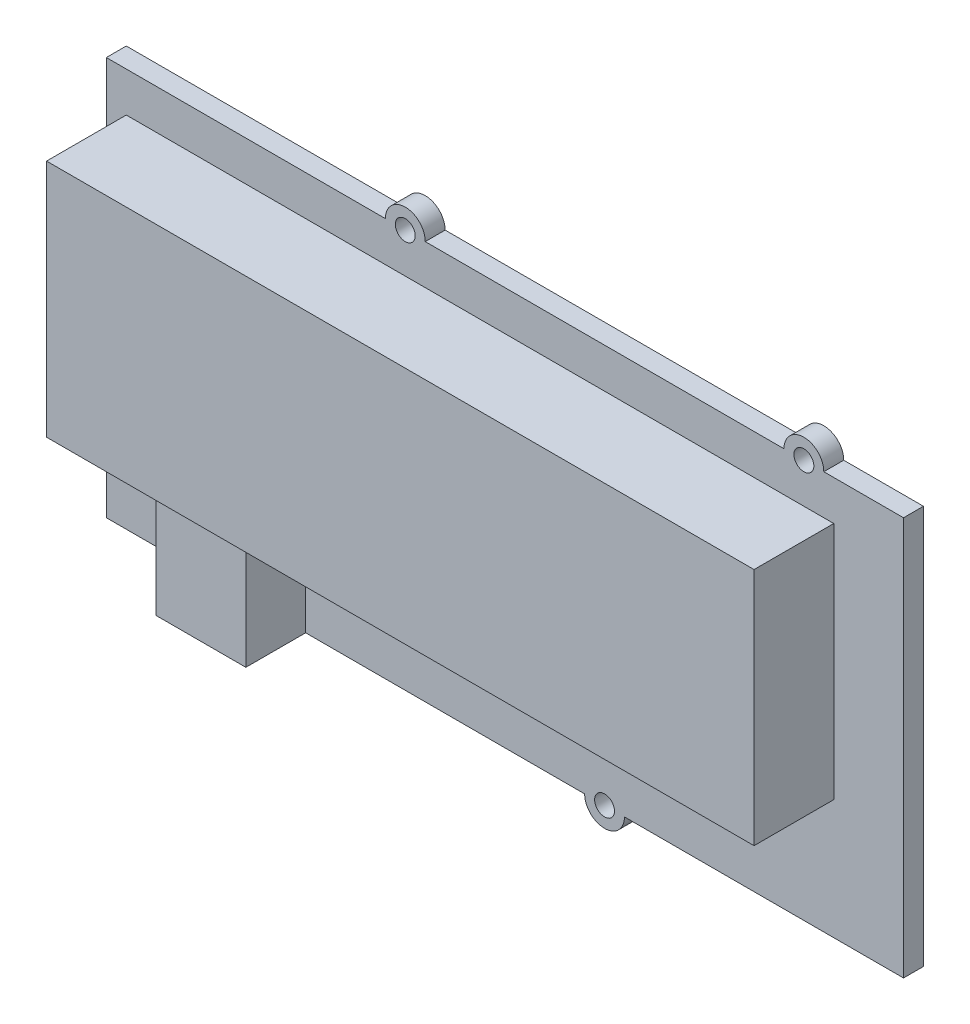
SolidWorks part; units mm, degrees
ref_plane "Plan de face" through (0, 0, 0) normal (0, 0, 1) x (1, 0, 0)
ref_plane "Plan de dessus" through (0, 0, 0) normal (0, 1, 0) x (1, 0, 0)
ref_plane "Plan de droite" through (0, 0, 0) normal (1, 0, 0) x (0, 0, -1)
sketch "Esquisse1" plane through (0, 0, 0) normal (0, 0, 1) x (1, 0, 0)
  line L0 (-47.6002, 9.7568) -> (-19.6002, 9.7568)
  line L2 (-47.6002, 9.7568) -> (-47.6002, -30.2432)
  line L4 (32.3998, 9.7568) -> (32.3998, -30.2432)
  line L5 (-15.6002, 9.7568) -> (20.3998, 9.7568)
  line L6 (24.3998, 9.7568) -> (32.3998, 9.7568)
  line L7 (32.3998, -30.2432) -> (4.3998, -30.2432)
  line L8 (-47.6002, -30.2432) -> (0.3998, -30.2432)
  circle A0 centre (22.3998, 9.7568) radius 1
  circle A1 centre (-17.6002, 9.7568) radius 1
  circle A2 centre (2.3998, -30.2432) radius 1
  arc A5 (-19.6002, 9.7568) -> (-15.6002, 9.7568) centre (-17.6002, 9.7568) cw
  arc A6 (20.3998, 9.7568) -> (24.3998, 9.7568) centre (22.3998, 9.7568) cw
  arc A8 (0.3998, -30.2432) -> (4.3998, -30.2432) centre (2.3998, -30.2432) ccw
  dimension "D3" = 2
  dimension "D5" = 2
  dimension "D7" = 2
  dimension "D8" = 30
  dimension "D1" = 80
  dimension "D2" = 40
  dimension "D4" = 10
  dimension "D6" = 40
extrude "Boss.-Extru.1" add sketch "Esquisse1" along normal blind 2 contours L8 A8 L7 L4 L6 A6 L5 A5 L0 L2 A0 A1 A2
sketch "Esquisse2" plane through (0, 0, 2) normal (0, 0, 1) x (1, 0, 0)
  line L0 (-47.6002, 9.7568) -> (-47.6002, -30.2432) construction
  line L1 (-45.6002, 5.7568) -> (25.3998, 5.7568)
  line L2 (-45.6002, 5.7568) -> (-45.6002, -18.2432)
  line L3 (-45.6002, -18.2432) -> (25.3998, -18.2432)
  line L4 (25.3998, 5.7568) -> (25.3998, -18.2432)
  line L5 (-47.6002, 9.7568) -> (-19.6002, 9.7568) construction
  dimension "D1" = 71
  dimension "D2" = 24
  dimension "D3" = 2
  dimension "D4" = 4
extrude "Boss.-Extru.3" add sketch "Esquisse2" along normal blind 8
sketch "Esquisse4" plane through (0, 0, 2) normal (0, 0, 1) x (1, 0, 0)
  line L0 (-45.6002, -18.2432) -> (25.3998, -18.2432) construction
  line L1 (-36.6002, -18.2432) -> (-27.6002, -18.2432)
  line L2 (-36.6002, -18.2432) -> (-36.6002, -30.2432)
  line L3 (-36.6002, -30.2432) -> (-27.6002, -30.2432)
  line L4 (-27.6002, -18.2432) -> (-27.6002, -30.2432)
  line L5 (-47.6002, -30.2432) -> (0.3998, -30.2432) construction
  line L6 (-47.6002, 9.7568) -> (-47.6002, -30.2432) construction
  dimension "D1" = 11
  dimension "D2" = 9
extrude "Boss.-Extru.4" add sketch "Esquisse4" along normal blind 6
